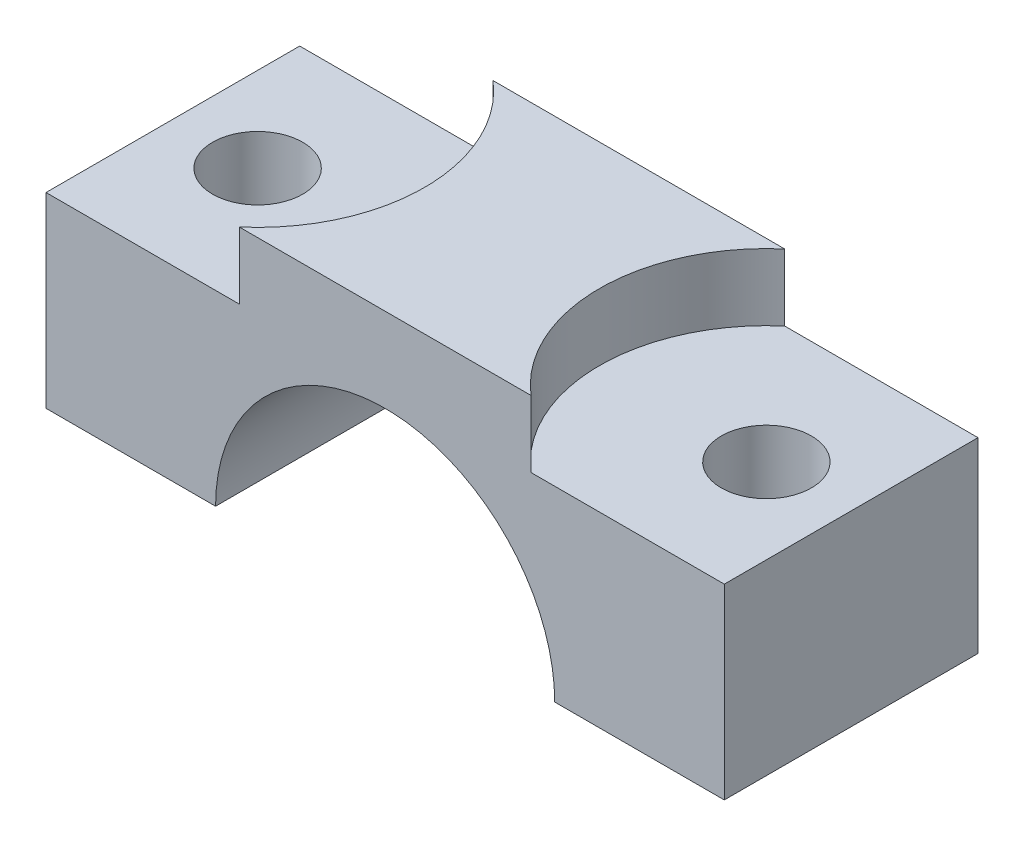
SolidWorks part; units mm, degrees
ref_plane "Front Plane" through (0, 0, 0) normal (0, 0, 1) x (1, 0, 0)
ref_plane "Top Plane" through (0, 0, 0) normal (0, 1, 0) x (1, 0, 0)
ref_plane "Right Plane" through (0, 0, 0) normal (1, 0, 0) x (0, 0, -1)
sketch "Sketch1" plane through (0, 0, 0) normal (0, 0, 1) x (1, 0, 0)
  line L0 (12.7, 0) -> (25.4, 0)
  line L1 (-25.4, 0) -> (-12.7, 0)
  line L2 (-25.4, 0) -> (-25.4, 19)
  line L3 (-25.4, 19) -> (25.4, 19)
  line L4 (25.4, 0) -> (25.4, 19)
  arc A0 (-12.7, 0) -> (12.7, 0) centre (0, 0) cw
  dimension "D1" = 50.8
  dimension "D3" = 12.7
  dimension "D2" = 19
extrude "Boss-Extrude1" add sketch "Sketch1" along normal mid plane 19 contours L3 L4 L0 A0 L1 L2
sketch "Sketch2" plane through (0, 0, 0) normal (0, -1, 0) x (1, 0, 0)
  line L0 (-19.05, 9.5) -> (-19.05, -9.5) construction
  line L1 (-25.4, 9.5) -> (-12.7, 9.5) construction
  line L2 (-25.4, -9.5) -> (-12.7, -9.5) construction
  line L3 (19.05, 9.5) -> (19.05, -9.5) construction
  line L4 (12.7, 9.5) -> (25.4, 9.5) construction
  line L5 (12.7, -9.5) -> (25.4, -9.5) construction
  point P12 (-19.05, 0)
  point P13 (19.05, 0)
hole_wizard "CBORE for M12 Hex Head Cap Screw1" positions "Sketch8" profile "Sketch9" counterbore size "M12" standard "ISO" end condition through all
sketch "Sketch8" plane through (0, 19, 0) normal (0, 1, 0) x (1, 0, 0)
  point P0 (19.05, 0)
  point P3 (-19.05, 0)
sketch "Sketch9" plane through (19.05, 19, 0) normal (1, 0, 0) x (0, 0, 1)
  line L0 (0, 0) -> (0, 19)
  line L1 (0, 19) -> (3.375, 19)
  line L3 (3.375, 19) -> (3.375, 5)
  line L4 (3.375, 5) -> (12.5, 5)
  line L5 (12.5, 5) -> (12.5, 0)
  line L7 (12.5, 0) -> (0, 0)
  line L11 (0, -6.35) -> (0, 107.95) construction
  dimension "Thru Hole Dia." = 6.75
  dimension "Thru Hole Depth" = 19
  dimension "C'Bore Dia." = 25
  dimension "C'Bore Depth" = 5
